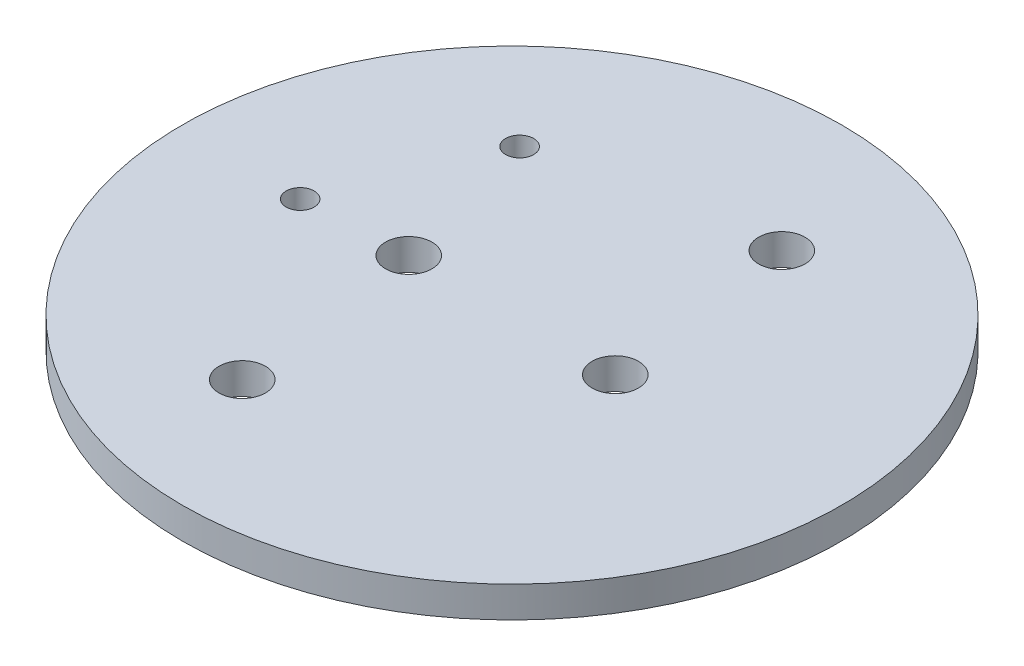
SolidWorks part; units mm, degrees
material "5052-H32"
ref_plane "Front Plane" through (0, 0, 0) normal (0, 0, 1) x (1, 0, 0)
ref_plane "Top Plane" through (0, 0, 0) normal (0, 1, 0) x (1, 0, 0)
ref_plane "Right Plane" through (0, 0, 0) normal (1, 0, 0) x (0, 0, -1)
sketch "Sketch1" plane through (0, 0, 0) normal (0, 1, 0) x (1, 0, 0)
  line L0 (12.1502, 29.3332) -> (-12.1502, -29.3332) construction
  line L1 (0, 0) -> (-41.7254, 0) construction
  circle A0 centre (0, 0) radius 50.673
  circle A1 centre (12.1502, 29.3332) radius 3.5687
  circle A2 centre (-12.1502, -29.3332) radius 3.5687
  circle A3 centre (-15.875, 0) radius 3.5687
  circle A4 centre (15.875, 0) radius 3.5687
  point P12 (0, 0)
  dimension "D1" = 101.346
  dimension "D2" = 7.1374
  dimension "D3" = 112.5
  dimension "D4" = 63.5
  dimension "D5" = 15.875
  dimension "D6" = 15.875
extrude "Boss-Extrude1" add sketch "Sketch1" along normal blind 4.7752
hole_wizard "#6 Clearance Hole1" positions "Sketch2" profile "Sketch3" hole size "#6" standard "ANSI Inch"
sketch "Sketch2" plane through (0, 4.7752, 0) normal (0, 1, 0) x (1, 0, 0)
  line L0 (-12.1502, -29.3332) -> (12.1502, 29.3332)
  line L5 (0, 0) -> (-21.8553, 23.0306)
  line L7 (0, 0) -> (29.3332, -12.1502)
  line L9 (0, 0) -> (-31.7391, -0.8311)
  circle A0 centre (0, 0) radius 31.75
  point P0 (-21.8553, 23.0306)
  point P2 (-31.7391, -0.8311)
  dimension "D1" = 66
sketch "Sketch3" plane through (-21.8553, 4.7752, -23.0306) normal (1, 0, 0) x (0, 0, 1)
  line L0 (0, 0) -> (0, 11.9614)
  line L1 (0, 11.9614) -> (2.1526, 10.668)
  line L2 (2.1526, 10.668) -> (2.1526, 0)
  line L5 (2.1526, 0) -> (0, 0)
  line L10 (0, 11.9614) -> (-2.1526, 10.668) construction
  line L11 (0, -6.35) -> (0, 107.95) construction
  dimension "Hole Dia." = 4.3053
  dimension "Hole Depth" = 10.668
  dimension "Drill Angle" = 118
